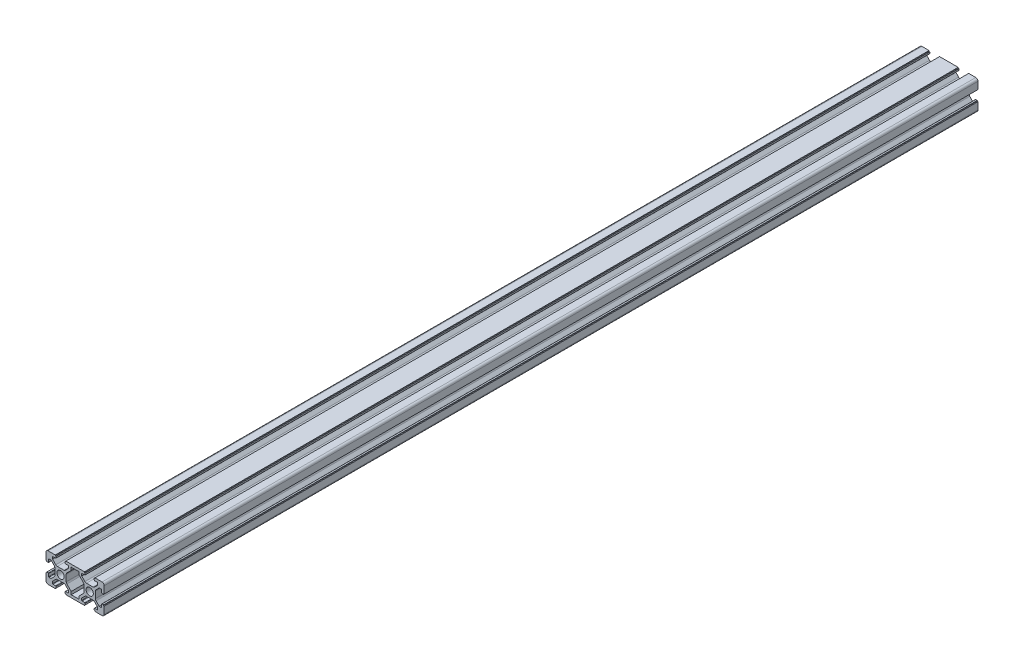
SolidWorks part; units mm, degrees
ref_plane "前视基准面" through (0, 0, 0) normal (0, 0, 1) x (1, 0, 0)
ref_plane "上视基准面" through (0, 0, 0) normal (0, 1, 0) x (1, 0, 0)
ref_plane "右视基准面" through (0, 0, 0) normal (1, 0, 0) x (0, 0, -1)
sketch "草图1" plane through (0, 0, 0) normal (0, 0, 1) x (1, 0, 0)
  line L0 (-1.9716, -6.6942) -> (-4.9322, -3.7335)
  line L1 (-5.3716, -2.6729) -> (-5.3716, 1.7645)
  line L2 (-4.9322, 2.8251) -> (-1.9716, 5.7858)
  line L3 (-0.7716, 9.5458) -> (-5.6716, 9.5458)
  line L4 (-5.6716, 9.5458) -> (-5.6716, 9.2458)
  line L5 (-5.8716, 9.0458) -> (-6.1716, 9.0458)
  line L6 (-6.1716, 9.0458) -> (-6.1716, 8.0458)
  line L7 (-5.8716, 7.7458) -> (-4.0716, 7.7458)
  line L8 (-3.7716, 7.4458) -> (-3.7716, 6.1058)
  line L9 (-3.7716, 6.1058) -> (-5.9922, 3.8851)
  line L10 (-7.0529, 3.4458) -> (-11.4903, 3.4458)
  line L11 (-12.5509, 3.8851) -> (-14.7716, 6.1058)
  line L12 (-14.7716, 6.1058) -> (-14.7716, 7.4458)
  line L13 (-14.4716, 7.7458) -> (-12.6716, 7.7458)
  line L14 (-12.3716, 8.0458) -> (-12.3716, 9.0458)
  line L15 (-12.3716, 9.0458) -> (-12.6716, 9.0458)
  line L16 (-12.8716, 9.2458) -> (-12.8716, 9.5458)
  line L17 (-12.8716, 9.5458) -> (-17.7716, 9.5458)
  line L18 (-19.2716, 8.0458) -> (-19.2716, 3.1458)
  line L19 (-19.2716, 3.1458) -> (-18.9716, 3.1458)
  line L20 (-18.7716, 2.9458) -> (-18.7716, 2.6458)
  line L21 (-18.7716, 2.6458) -> (-17.7716, 2.6458)
  line L22 (-17.4716, 2.9458) -> (-17.4716, 4.7458)
  line L23 (-17.1716, 5.0458) -> (-15.8316, 5.0458)
  line L24 (-15.8316, 5.0458) -> (-13.6109, 2.8251)
  line L25 (-13.1716, 1.7645) -> (-13.1716, -2.6729)
  line L26 (-13.6109, -3.7335) -> (-15.8316, -5.9542)
  line L27 (-15.8316, -5.9542) -> (-17.1716, -5.9542)
  line L28 (-17.4716, -5.6542) -> (-17.4716, -3.8542)
  line L29 (-17.7716, -3.5542) -> (-18.7716, -3.5542)
  line L30 (-18.7716, -3.5542) -> (-18.7716, -3.8542)
  line L31 (-18.9716, -4.0542) -> (-19.2716, -4.0542)
  line L32 (-19.2716, -4.0542) -> (-19.2716, -8.9542)
  line L33 (-17.7716, -10.4542) -> (-12.8716, -10.4542)
  line L34 (-12.8716, -10.4542) -> (-12.8716, -10.1542)
  line L35 (-12.6716, -9.9542) -> (-12.3716, -9.9542)
  line L36 (-12.3716, -9.9542) -> (-12.3716, -8.9542)
  line L37 (-12.6716, -8.6542) -> (-14.4716, -8.6542)
  line L38 (-14.7716, -8.3542) -> (-14.7716, -7.0142)
  line L39 (-14.7716, -7.0142) -> (-12.5509, -4.7935)
  line L40 (-11.4903, -4.3542) -> (-7.0529, -4.3542)
  line L41 (-5.9922, -4.7935) -> (-3.7716, -7.0142)
  line L42 (-3.7716, -7.0142) -> (-3.7716, -8.3542)
  line L43 (-4.0716, -8.6542) -> (-5.8716, -8.6542)
  line L44 (-6.1716, -8.9542) -> (-6.1716, -9.9542)
  line L45 (-6.1716, -9.9542) -> (-5.8716, -9.9542)
  line L46 (-5.6716, -10.1542) -> (-5.6716, -10.4542)
  line L47 (-5.6716, -10.4542) -> (-0.7716, -10.4542)
  line L48 (-0.7716, -10.4542) -> (7.1284, -10.4542)
  line L49 (7.1284, -10.4542) -> (7.1284, -10.1542)
  line L50 (7.3284, -9.9542) -> (7.6284, -9.9542)
  line L51 (7.6284, -9.9542) -> (7.6284, -8.9542)
  line L52 (7.3284, -8.6542) -> (5.5284, -8.6542)
  line L53 (5.2284, -8.3542) -> (5.2284, -7.0142)
  line L54 (5.2284, -7.0142) -> (7.4491, -4.7935)
  line L55 (8.5097, -4.3542) -> (12.9471, -4.3542)
  line L56 (14.0078, -4.7935) -> (16.2284, -7.0142)
  line L57 (16.2284, -7.0142) -> (16.2284, -8.3542)
  line L58 (15.9284, -8.6542) -> (14.1284, -8.6542)
  line L59 (13.8284, -8.9542) -> (13.8284, -9.9542)
  line L60 (13.8284, -9.9542) -> (14.1284, -9.9542)
  line L61 (14.3284, -10.1542) -> (14.3284, -10.4542)
  line L62 (14.3284, -10.4542) -> (19.2284, -10.4542)
  line L63 (20.7284, -8.9542) -> (20.7284, -4.0542)
  line L64 (20.7284, -4.0542) -> (20.4284, -4.0542)
  line L65 (20.2284, -3.8542) -> (20.2284, -3.5542)
  line L66 (20.2284, -3.5542) -> (19.2284, -3.5542)
  line L67 (18.9284, -3.8542) -> (18.9284, -5.6542)
  line L68 (18.6284, -5.9542) -> (17.2884, -5.9542)
  line L69 (17.2884, -5.9542) -> (15.0678, -3.7335)
  line L70 (14.6284, -2.6729) -> (14.6284, 1.7645)
  line L71 (15.0678, 2.8251) -> (17.2884, 5.0458)
  line L72 (17.2884, 5.0458) -> (18.6284, 5.0458)
  line L73 (18.9284, 4.7458) -> (18.9284, 2.9458)
  line L74 (19.2284, 2.6458) -> (20.2284, 2.6458)
  line L75 (20.2284, 2.6458) -> (20.2284, 2.9458)
  line L76 (20.4284, 3.1458) -> (20.7284, 3.1458)
  line L77 (20.7284, 3.1458) -> (20.7284, 8.0458)
  line L78 (19.2284, 9.5458) -> (14.3284, 9.5458)
  line L79 (14.3284, 9.5458) -> (14.3284, 9.2458)
  line L80 (14.1284, 9.0458) -> (13.8284, 9.0458)
  line L81 (13.8284, 9.0458) -> (13.8284, 8.0458)
  line L82 (14.1284, 7.7458) -> (15.9284, 7.7458)
  line L83 (16.2284, 7.4458) -> (16.2284, 6.1058)
  line L84 (16.2284, 6.1058) -> (14.0078, 3.8851)
  line L85 (12.9471, 3.4458) -> (8.5097, 3.4458)
  line L86 (7.4491, 3.8851) -> (5.2284, 6.1058)
  line L87 (5.2284, 6.1058) -> (5.2284, 7.4458)
  line L88 (5.5284, 7.7458) -> (7.3284, 7.7458)
  line L89 (7.6284, 8.0458) -> (7.6284, 9.0458)
  line L90 (7.6284, 9.0458) -> (7.3284, 9.0458)
  line L91 (7.1284, 9.2458) -> (7.1284, 9.5458)
  line L92 (7.1284, 9.5458) -> (2.2284, 9.5458)
  line L93 (3.4284, 5.7858) -> (6.3891, 2.8251)
  line L94 (6.8284, 1.7645) -> (6.8284, -2.6729)
  line L95 (6.3891, -3.7335) -> (3.4284, -6.6942)
  line L96 (-0.7716, 9.5458) -> (2.2284, 9.5458)
  line L99 (-1.9716, 7.7458) -> (3.4284, 7.7458)
  line L100 (3.4284, 7.7458) -> (3.4284, 5.7858)
  line L101 (-1.9716, 7.7458) -> (-1.9716, 5.7858)
  line L102 (-1.9716, -8.6542) -> (3.4284, -8.6542)
  line L103 (3.4284, -8.6542) -> (3.4284, -6.6942)
  line L104 (-1.9716, -8.6542) -> (-1.9716, -6.6942)
  arc A1 (-5.3716, -2.6729) -> (-4.9322, -3.7335) centre (-3.8716, -2.6729) ccw
  arc A2 (-4.9322, 2.8251) -> (-5.3716, 1.7645) centre (-3.8716, 1.7645) ccw
  arc A3 (-5.8716, 9.0458) -> (-5.6716, 9.2458) centre (-5.8716, 9.2458) ccw
  arc A4 (-6.1716, 8.0458) -> (-5.8716, 7.7458) centre (-5.8716, 8.0458) ccw
  arc A5 (-3.7716, 7.4458) -> (-4.0716, 7.7458) centre (-4.0716, 7.4458) ccw
  arc A6 (-7.0529, 3.4458) -> (-5.9922, 3.8851) centre (-7.0529, 4.9458) ccw
  arc A7 (-12.5509, 3.8851) -> (-11.4903, 3.4458) centre (-11.4903, 4.9458) ccw
  arc A8 (-14.4716, 7.7458) -> (-14.7716, 7.4458) centre (-14.4716, 7.4458) ccw
  arc A9 (-12.6716, 7.7458) -> (-12.3716, 8.0458) centre (-12.6716, 8.0458) ccw
  arc A10 (-12.8716, 9.2458) -> (-12.6716, 9.0458) centre (-12.6716, 9.2458) ccw
  arc A11 (-17.7716, 9.5458) -> (-19.2716, 8.0458) centre (-17.7716, 8.0458) ccw
  arc A12 (-18.7716, 2.9458) -> (-18.9716, 3.1458) centre (-18.9716, 2.9458) ccw
  arc A13 (-17.7716, 2.6458) -> (-17.4716, 2.9458) centre (-17.7716, 2.9458) ccw
  arc A14 (-17.1716, 5.0458) -> (-17.4716, 4.7458) centre (-17.1716, 4.7458) ccw
  arc A15 (-13.1716, 1.7645) -> (-13.6109, 2.8251) centre (-14.6716, 1.7645) ccw
  arc A16 (-13.6109, -3.7335) -> (-13.1716, -2.6729) centre (-14.6716, -2.6729) ccw
  arc A17 (-17.4716, -5.6542) -> (-17.1716, -5.9542) centre (-17.1716, -5.6542) ccw
  arc A18 (-17.4716, -3.8542) -> (-17.7716, -3.5542) centre (-17.7716, -3.8542) ccw
  arc A19 (-18.9716, -4.0542) -> (-18.7716, -3.8542) centre (-18.9716, -3.8542) ccw
  arc A20 (-19.2716, -8.9542) -> (-17.7716, -10.4542) centre (-17.7716, -8.9542) ccw
  arc A21 (-12.6716, -9.9542) -> (-12.8716, -10.1542) centre (-12.6716, -10.1542) ccw
  arc A22 (-12.3716, -8.9542) -> (-12.6716, -8.6542) centre (-12.6716, -8.9542) ccw
  arc A23 (-14.7716, -8.3542) -> (-14.4716, -8.6542) centre (-14.4716, -8.3542) ccw
  arc A24 (-11.4903, -4.3542) -> (-12.5509, -4.7935) centre (-11.4903, -5.8542) ccw
  arc A25 (-5.9922, -4.7935) -> (-7.0529, -4.3542) centre (-7.0529, -5.8542) ccw
  arc A26 (-4.0716, -8.6542) -> (-3.7716, -8.3542) centre (-4.0716, -8.3542) ccw
  arc A27 (-5.8716, -8.6542) -> (-6.1716, -8.9542) centre (-5.8716, -8.9542) ccw
  arc A28 (-5.6716, -10.1542) -> (-5.8716, -9.9542) centre (-5.8716, -10.1542) ccw
  arc A29 (7.3284, -9.9542) -> (7.1284, -10.1542) centre (7.3284, -10.1542) ccw
  arc A30 (7.6284, -8.9542) -> (7.3284, -8.6542) centre (7.3284, -8.9542) ccw
  arc A31 (5.2284, -8.3542) -> (5.5284, -8.6542) centre (5.5284, -8.3542) ccw
  arc A32 (8.5097, -4.3542) -> (7.4491, -4.7935) centre (8.5097, -5.8542) ccw
  arc A33 (14.0078, -4.7935) -> (12.9471, -4.3542) centre (12.9471, -5.8542) ccw
  arc A34 (15.9284, -8.6542) -> (16.2284, -8.3542) centre (15.9284, -8.3542) ccw
  arc A35 (14.1284, -8.6542) -> (13.8284, -8.9542) centre (14.1284, -8.9542) ccw
  arc A36 (14.3284, -10.1542) -> (14.1284, -9.9542) centre (14.1284, -10.1542) ccw
  arc A37 (19.2284, -10.4542) -> (20.7284, -8.9542) centre (19.2284, -8.9542) ccw
  arc A38 (20.2284, -3.8542) -> (20.4284, -4.0542) centre (20.4284, -3.8542) ccw
  arc A39 (19.2284, -3.5542) -> (18.9284, -3.8542) centre (19.2284, -3.8542) ccw
  arc A40 (18.6284, -5.9542) -> (18.9284, -5.6542) centre (18.6284, -5.6542) ccw
  arc A41 (14.6284, -2.6729) -> (15.0678, -3.7335) centre (16.1284, -2.6729) ccw
  arc A42 (15.0678, 2.8251) -> (14.6284, 1.7645) centre (16.1284, 1.7645) ccw
  arc A43 (18.9284, 4.7458) -> (18.6284, 5.0458) centre (18.6284, 4.7458) ccw
  arc A44 (18.9284, 2.9458) -> (19.2284, 2.6458) centre (19.2284, 2.9458) ccw
  arc A45 (20.4284, 3.1458) -> (20.2284, 2.9458) centre (20.4284, 2.9458) ccw
  arc A46 (20.7284, 8.0458) -> (19.2284, 9.5458) centre (19.2284, 8.0458) ccw
  arc A47 (14.1284, 9.0458) -> (14.3284, 9.2458) centre (14.1284, 9.2458) ccw
  arc A48 (13.8284, 8.0458) -> (14.1284, 7.7458) centre (14.1284, 8.0458) ccw
  arc A49 (16.2284, 7.4458) -> (15.9284, 7.7458) centre (15.9284, 7.4458) ccw
  arc A50 (12.9471, 3.4458) -> (14.0078, 3.8851) centre (12.9471, 4.9458) ccw
  arc A51 (7.4491, 3.8851) -> (8.5097, 3.4458) centre (8.5097, 4.9458) ccw
  arc A52 (5.5284, 7.7458) -> (5.2284, 7.4458) centre (5.5284, 7.4458) ccw
  arc A53 (7.3284, 7.7458) -> (7.6284, 8.0458) centre (7.3284, 8.0458) ccw
  arc A54 (7.1284, 9.2458) -> (7.3284, 9.0458) centre (7.3284, 9.2458) ccw
  arc A55 (6.8284, 1.7645) -> (6.3891, 2.8251) centre (5.3284, 1.7645) ccw
  arc A56 (6.3891, -3.7335) -> (6.8284, -2.6729) centre (5.3284, -2.6729) ccw
  circle A58 centre (10.7284, -0.4542) radius 2.5
  circle A63 centre (-9.2716, -0.4542) radius 2.5
extrude "凸台-拉伸1" add sketch "草图1" along normal blind 600
